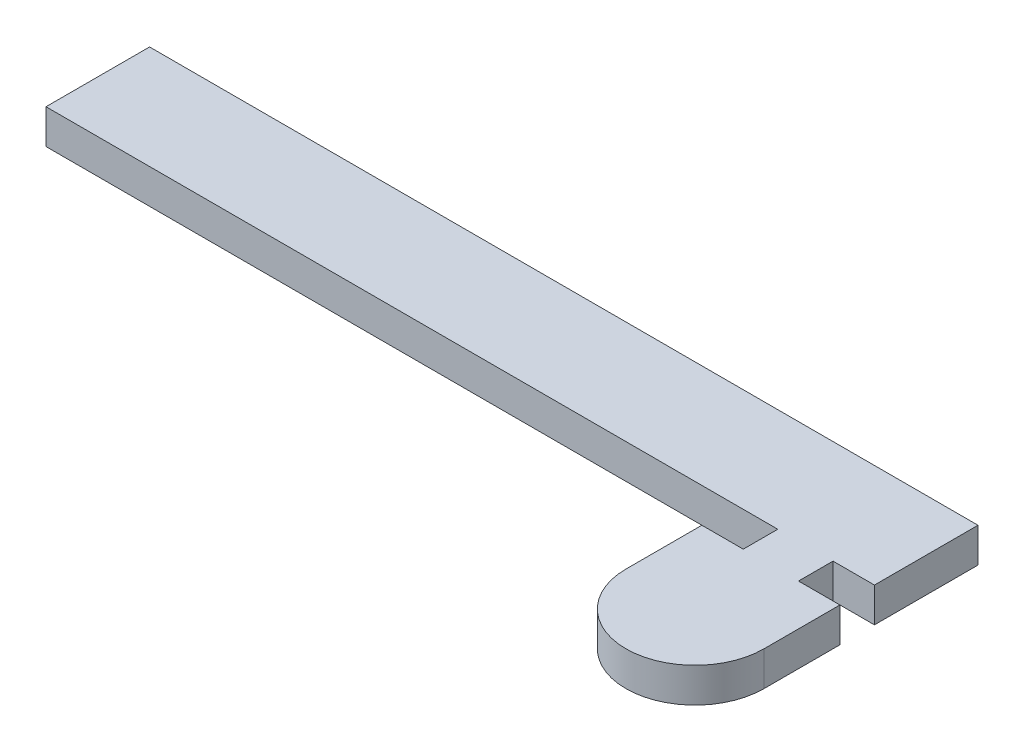
SolidWorks part; units mm, degrees
ref_plane "Plano frontal" through (0, 0, 0) normal (0, 0, 1) x (1, 0, 0)
ref_plane "Plano superior" through (0, 0, 0) normal (0, 1, 0) x (1, 0, 0)
ref_plane "Plano direito" through (0, 0, 0) normal (1, 0, 0) x (0, 0, -1)
sketch "Esboço1" plane through (0, 0, 0) normal (0, 1, 0) x (1, 0, 0)
  line L1 (-37.8393, -5.269) -> (-17.8393, -5.269)
  line L2 (-37.8393, -5.269) -> (-37.8393, -21.269)
  line L3 (-37.8393, -21.269) -> (-17.8393, -21.269)
  line L4 (-17.8393, -5.269) -> (-17.8393, -21.269)
  circle A0 centre (-27.8393, -21.269) radius 10
extrude "Ressalto-extrusão1" add sketch "Esboço1" along normal blind 5 contours L3 A0 | L3 A0 | A0 L4 L1 L2
sketch "Esboço2" plane through (0, 5, 0) normal (0, 1, 0) x (1, 0, 0)
  line L1 (-37.8393, -5.269) -> (-31.8393, -5.269)
  line L2 (-37.8393, -5.269) -> (-37.8393, -10.269)
  line L3 (-37.8393, -10.269) -> (-31.8393, -10.269)
  line L4 (-31.8393, -5.269) -> (-31.8393, -10.269)
  line L5 (-17.8393, -5.269) -> (-23.8393, -5.269)
  line L6 (-17.8393, -5.269) -> (-17.8393, -10.269)
  line L7 (-17.8393, -10.269) -> (-23.8393, -10.269)
  line L8 (-23.8393, -5.269) -> (-23.8393, -10.269)
extrude "Corte-extrusão1" cut sketch "Esboço2" against normal blind 10
sketch "Esboço3" plane through (0, 5, 0) normal (0, 1, 0) x (1, 0, 0)
  line L0 (-17.8393, 9.731) -> (-137.8393, 9.731)
  line L1 (-17.8393, -5.269) -> (-137.8393, -5.269)
  line L2 (-17.8393, -5.269) -> (-17.8393, 9.731)
  line L3 (-137.8393, 9.731) -> (-137.8393, -5.269)
extrude "Ressalto-extrusão2" add sketch "Esboço3" against normal blind 5 contours L0 L3 L1 L2
